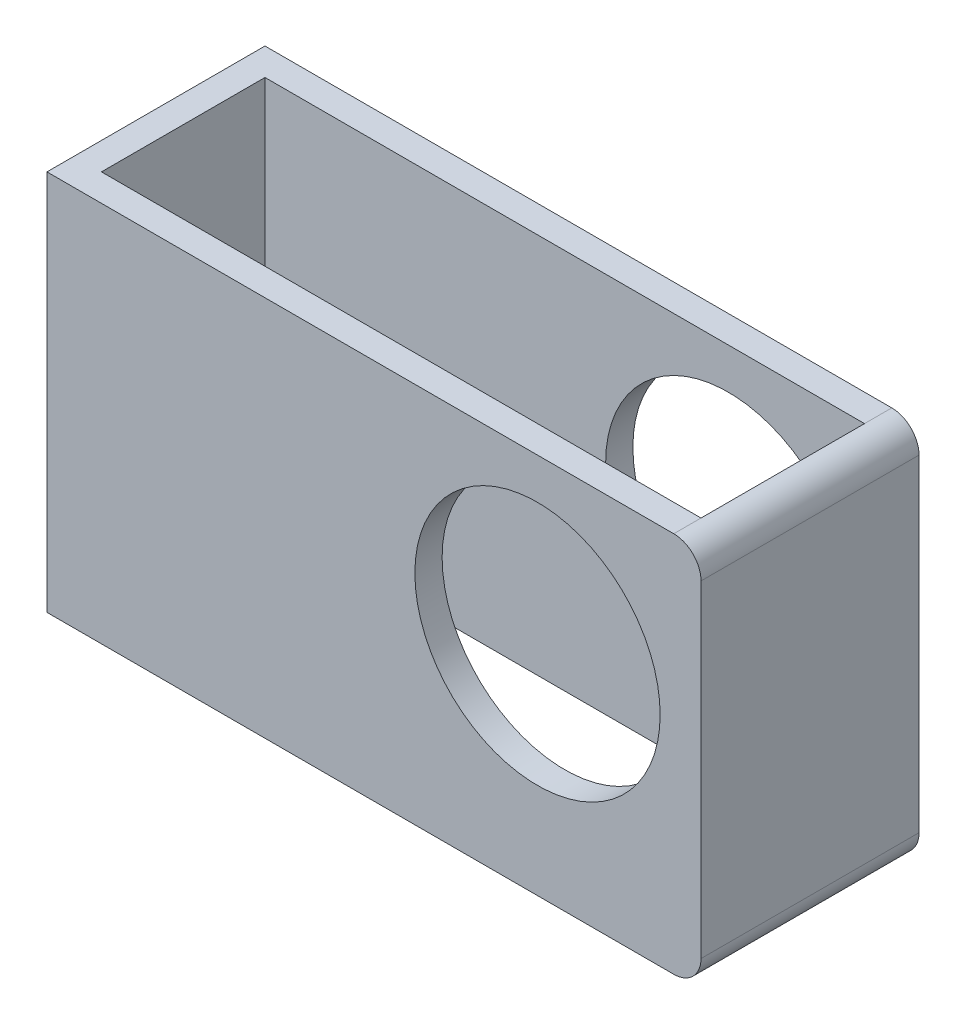
SolidWorks part; units mm, degrees
ref_plane "Front Plane" through (0, 0, 0) normal (0, 0, 1) x (1, 0, 0)
ref_plane "Top Plane" through (0, 0, 0) normal (0, 1, 0) x (1, 0, 0)
ref_plane "Right Plane" through (0, 0, 0) normal (1, 0, 0) x (0, 0, -1)
sketch "Sketch1" plane through (0, 0, 0) normal (0, 0, 1) x (1, 0, 0)
  line L1 (-38.1, 22.225) -> (38.1, 22.225)
  line L2 (-38.1, 22.225) -> (-38.1, -22.225)
  line L3 (-38.1, -22.225) -> (38.1, -22.225)
  line L4 (38.1, 22.225) -> (38.1, -22.225)
  line L5 (-38.1, 22.225) -> (38.1, -22.225) construction
  line L6 (-38.1, -22.225) -> (38.1, 22.225) construction
  circle A0 centre (19.05, 3.175) radius 14.2875
  point P0 (0, 0)
  dimension "D3" = 57.15
  dimension "D4" = 25.4
  dimension "D5" = 28.575
  dimension "D1" = 44.45
  dimension "D2" = 76.2
extrude "Boss-Extrude1" add sketch "Sketch1" along normal mid plane 25.4
fillet "Fillet1" radius 3.175 2 edges at (38.1, -22.225, 0) (38.1, 22.225, 0)
sketch "Sketch3" plane through (0, -22.225, 0) normal (0, -1, 0) x (1, 0, 0)
  line L27 (-34.925, 9.525) -> (-34.925, -9.525)
  line L28 (-34.925, -9.525) -> (34.925, -9.525)
  line L30 (34.925, -9.525) -> (34.925, 9.525)
  line L32 (34.925, 9.525) -> (-34.925, 9.525)
  line L33 (-34.925, 9.525) -> (-34.925, -9.525)
  line L34 (-34.925, -9.525) -> (34.925, -9.525)
  line L36 (34.925, -9.525) -> (34.925, 9.525)
  line L38 (34.925, 9.525) -> (-34.925, 9.525)
  dimension "D1" = 3.175
extrude "Cut-Extrude2" cut sketch "Sketch3" against normal through all
hole_wizard "1/4 (0.25) Diameter Hole1" positions "Sketch5" profile "Sketch6" hole size "1/4" standard "ANSI Inch"
sketch "Sketch5" plane through (-38.1, 0, 0) normal (-1, 0, 0) x (0, 0, 1)
  line L0 (12.7, -22.225) -> (-12.7, -22.225) construction
  point P0 (0, 6.35)
  point P2 (0, -12.7)
  dimension "D1" = 9.525
  dimension "D2" = 19.05
sketch "Sketch6" plane through (-38.1, 6.35, 0) normal (0, 1, 0) x (0, 0, 1)
  line L0 (0, 0) -> (0, 6.9877)
  line L1 (0, 6.9877) -> (3.175, 5.08)
  line L2 (3.175, 5.08) -> (3.175, 0)
  line L5 (3.175, 0) -> (0, 0)
  line L10 (0, 6.9877) -> (-3.175, 5.08) construction
  line L11 (0, -6.35) -> (0, 107.95) construction
  dimension "Hole Dia." = 6.35
  dimension "Hole Depth" = 5.08
  dimension "Drill Angle" = 118
